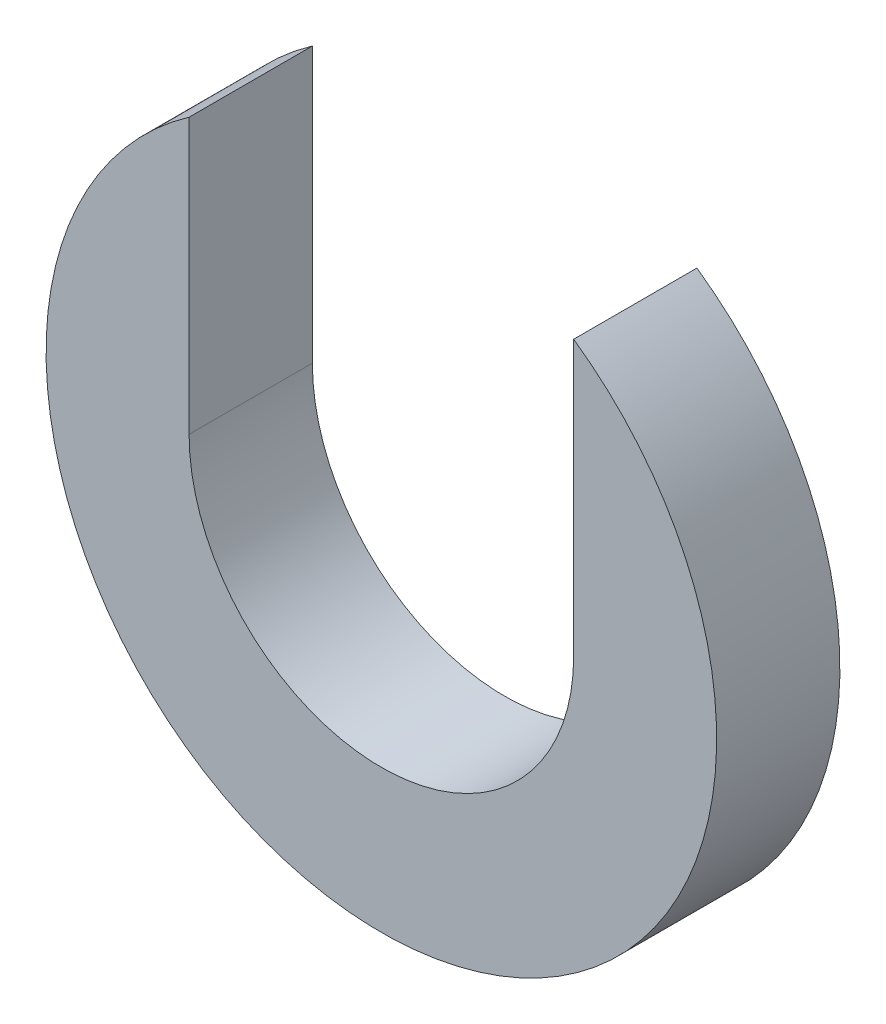
SolidWorks part; units mm, degrees
ref_plane "Front Plane" through (0, 0, 0) normal (0, 0, 1) x (1, 0, 0)
ref_plane "Top Plane" through (0, 0, 0) normal (0, 1, 0) x (1, 0, 0)
ref_plane "Right Plane" through (0, 0, 0) normal (1, 0, 0) x (0, 0, -1)
sketch "Sketch1" plane through (0, 0, 0) normal (0, 0, 1) x (1, 0, 0)
  line L0 (-4.953, 0) -> (-4.953, 7.0745)
  line L1 (4.953, 0) -> (4.953, 7.0745)
  arc A0 (-4.953, 7.0745) -> (4.953, 7.0745) centre (0, 0) ccw
  arc A1 (-4.953, 0) -> (4.953, 0) centre (0, 0) ccw
  dimension "D1" = 17.272
extrude "Boss-Extrude1" add sketch "Sketch1" along normal blind 3.175
